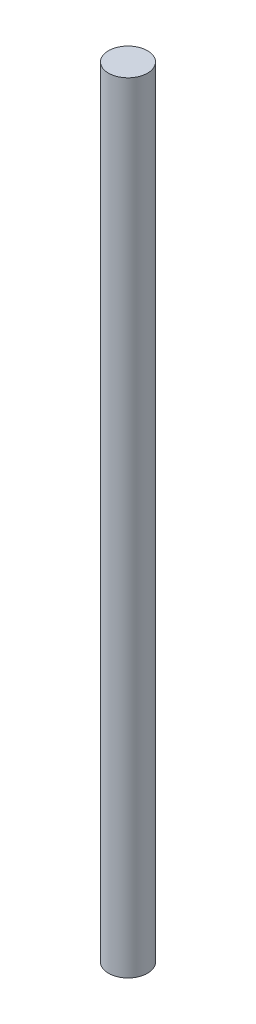
SolidWorks part; units mm, degrees
ref_plane "Front Plane" through (0, 0, 0) normal (0, 0, 1) x (1, 0, 0)
ref_plane "Top Plane" through (0, 0, 0) normal (0, 1, 0) x (1, 0, 0)
ref_plane "Right Plane" through (0, 0, 0) normal (1, 0, 0) x (0, 0, -1)
sketch "Sketch1" plane through (0, 0, 0) normal (0, 1, 0) x (1, 0, 0)
  circle A0 centre (0, 0) radius 2.5
  dimension "D1" = 5
extrude "Boss-Extrude1" add sketch "Sketch1" along normal blind 100
